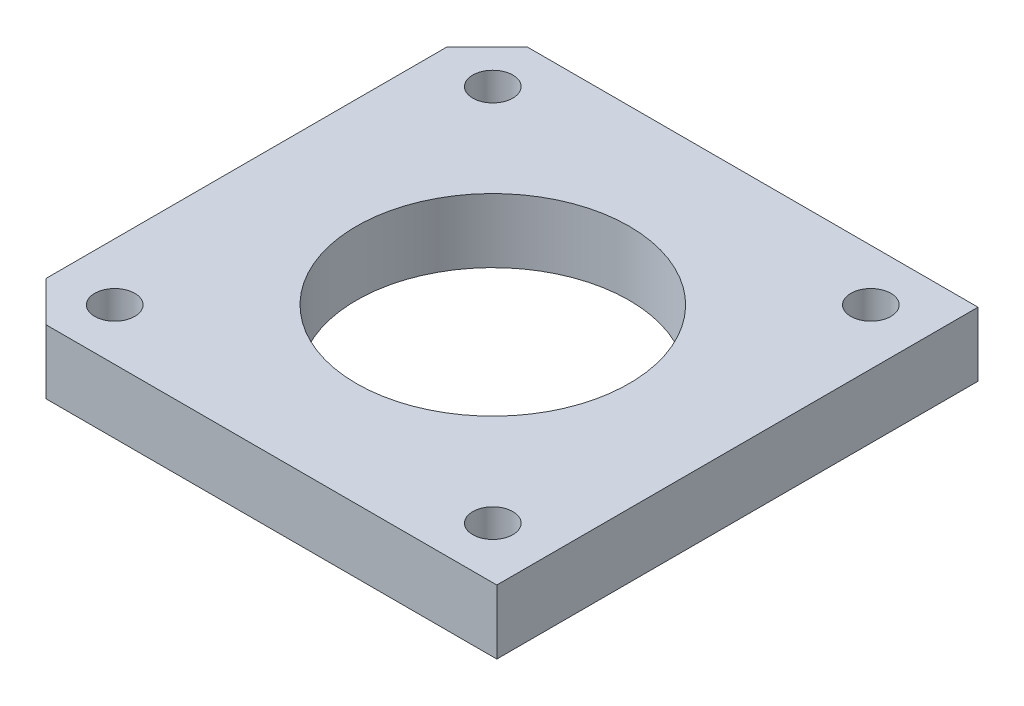
SolidWorks part; units mm, degrees
ref_plane "Front Plane" through (0, 0, 0) normal (0, 0, 1) x (1, 0, 0)
ref_plane "Top Plane" through (0, 0, 0) normal (0, 1, 0) x (1, 0, 0)
ref_plane "Right Plane" through (0, 0, 0) normal (1, 0, 0) x (0, 0, -1)
sketch "Sketch2" plane through (0, 0, 0) normal (0, 1, 0) x (1, 0, 0)
  line L1 (-18.7102, -30) -> (42.5, -30)
  line L2 (-18.7102, -30) -> (-18.7102, 30)
  line L3 (-18.7102, 30) -> (42.5, 30)
  line L4 (42.5, -30) -> (42.5, 30)
  point P0 (0, 0)
extrude "Extrude1" add sketch "Sketch2" along normal blind 8
chamfer "Chamfer1" distance 5 angle 45 2 edges at (-18.7102, 4, -30) (-18.7102, 4, 30)
sketch "Sketch3" plane through (0, 8, 0) normal (0, 1, 0) x (1, 0, 0)
  circle A0 centre (12, 0) radius 17
  circle A1 centre (-11.57, 23.57) radius 2.5
  circle A2 centre (35.57, 23.57) radius 2.5
  circle A3 centre (-11.57, -23.57) radius 2.5
  circle A4 centre (35.57, -23.57) radius 2.5
extrude "Cut-Extrude1" cut sketch "Sketch3" against normal through all
